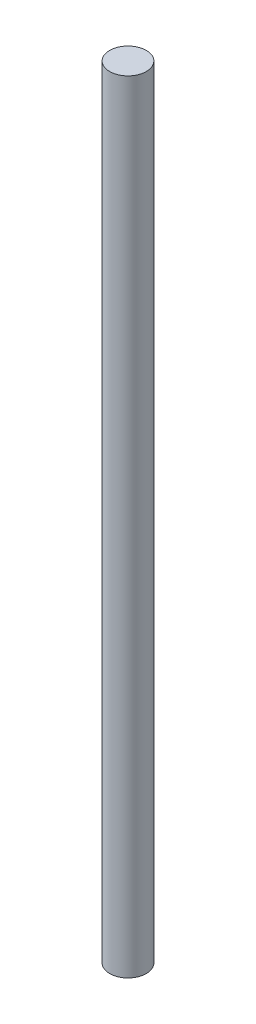
SolidWorks part; units mm, degrees
material "Aluminium"
ref_plane "Ebene vorne" through (0, 0, 0) normal (1, 0, 0) x (0, 1, 0)
ref_plane "Ebene oben" through (0, 0, 0) normal (0, 0, 1) x (0, 1, 0)
ref_plane "Ebene rechts" through (0, 0, 0) normal (0, 1, 0) x (-1, 0, 0)
sketch "Skizze1" plane through (0, 0, 0) normal (0, 1, 0) x (-1, 0, 0)
  circle A0 centre (0, 0) radius 3
extrude "Aufsatz-Linear austragen1" add sketch "Skizze1" along normal blind 128
